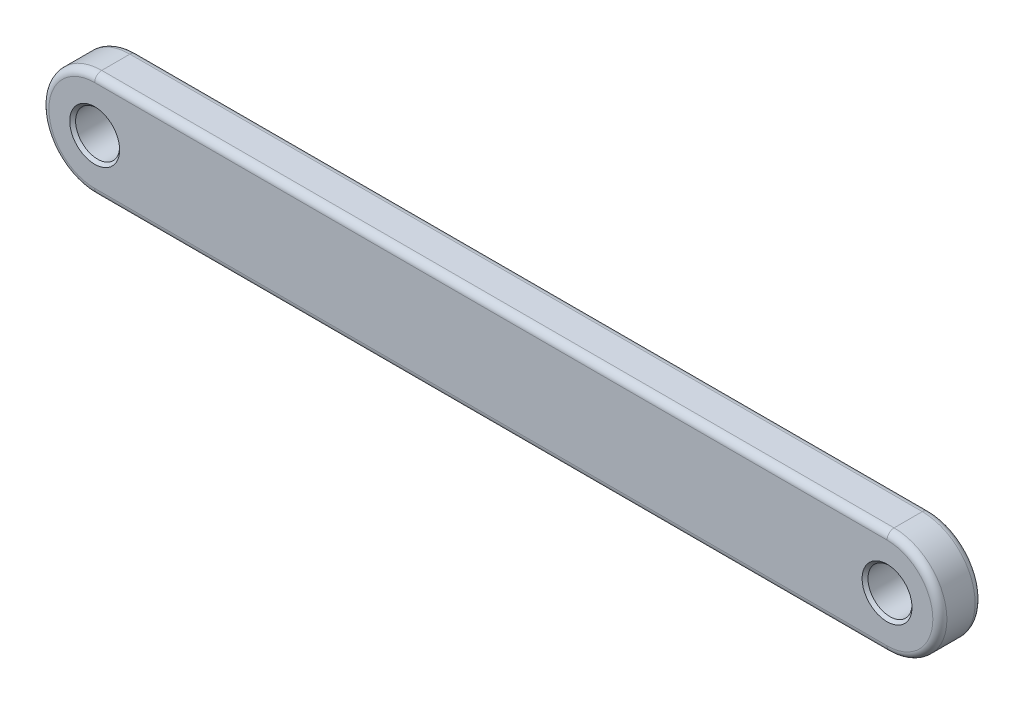
SolidWorks part; units mm, degrees
ref_plane "Front Plane" through (0, 0, 0) normal (0, 0, 1) x (1, 0, 0)
ref_plane "Top Plane" through (0, 0, 0) normal (0, 1, 0) x (1, 0, 0)
ref_plane "Right Plane" through (0, 0, 0) normal (1, 0, 0) x (0, 0, -1)
sketch "Sketch1" plane through (0, 0, 0) normal (0, 0, 1) x (1, 0, 0)
  line L0 (-71.4375, 0) -> (71.4375, 0) construction
  line L1 (-71.4375, 9.525) -> (71.4375, 9.525)
  line L2 (-71.4375, -9.525) -> (71.4375, -9.525)
  arc A0 (-71.4375, 9.525) -> (-71.4375, -9.525) centre (-71.4375, 0) ccw
  arc A1 (71.4375, -9.525) -> (71.4375, 9.525) centre (71.4375, 0) ccw
  circle A2 centre (-71.4375, 0) radius 3.9687
  circle A3 centre (71.4375, 0) radius 3.9687
  point P2 (0, 0)
  dimension "D1" = 9.525
  dimension "D2" = 7.9375
  dimension "D3" = 142.875
  dimension "D4" = 7.9375
extrude "Boss-Extrude1" add sketch "Sketch1" along normal blind 7.62
fillet "Fillet1" radius 1.27 8 edges at (80.9625, 0, 0) (0, -9.525, 0) (-80.9625, 0, 0) (80.9625, 0, 7.62) (0, -9.525, 7.62) (-80.9625, 0, 7.62) (0, 9.525, 0) (0, 9.525, 7.62)
sketch "Sketch2" plane through (0, 0, 0) normal (0, 0, -1) x (-1, 0, 0)
  circle A0 centre (-71.4375, 0) radius 3.9687 construction
  circle A1 centre (-71.4375, 0) radius 3.9687
  circle A2 centre (-71.4375, 0) radius 5.5563
  dimension "D1" = 1.5875
extrude "Boss-Extrude2" add sketch "Sketch2" along normal blind 2.1167
fillet "Fillet2" radius 1.5875 1 edges at (76.9938, 0, 0)
chamfer "Chamfer1" distance 0.5292 angle 45 4 edges at (-67.4688, 0, 0) (67.4688, 0, -2.1167) (-67.4688, 0, 7.62) (75.4062, 0, 7.62)
fillet "Fillet3" radius 0.3969 1 edges at (65.8813, 0, -2.1167)
